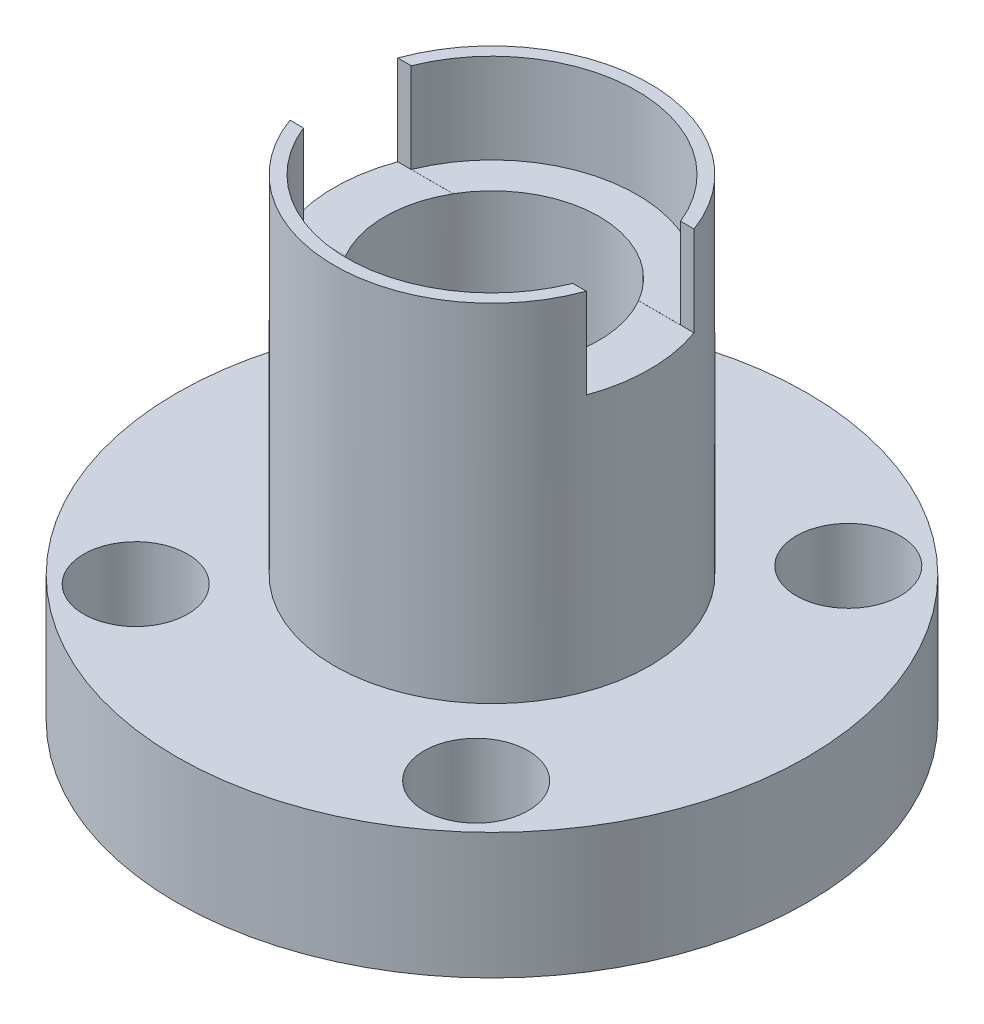
SolidWorks part; units mm, degrees
ref_plane "前视基准面" through (0, 0, 0) normal (0, 0, 1) x (1, 0, 0)
ref_plane "上视基准面" through (0, 0, 0) normal (0, 1, 0) x (1, 0, 0)
ref_plane "右视基准面" through (0, 0, 0) normal (1, 0, 0) x (0, 0, -1)
sketch "草图1" plane through (0, 0, 0) normal (0, 1, 0) x (1, 0, 0)
  circle A0 centre (0, 0) radius 10
extrude "凸台-拉伸1" add sketch "草图1" along normal blind 4
sketch "草图2" plane through (0, 0, 0) normal (0, -1, 0) x (1, 0, 0)
  line L1 (-5.4001, 5.9024) -> (5.4001, 5.9024) construction
  line L2 (-5.4001, 5.9024) -> (-5.4001, -5.9024) construction
  line L3 (-5.4001, -5.9024) -> (5.4001, -5.9024) construction
  line L4 (5.4001, 5.9024) -> (5.4001, -5.9024) construction
  line L5 (0, -5.9024) -> (0, 5.9024) construction
  line L6 (-5.4001, 0) -> (5.4001, 0) construction
  point P0 (0, 0)
  dimension "D1" = 16
  dimension "D2" = 16
sketch "草图4" plane through (0, 0, 0) normal (0, -1, 0) x (-1, 0, 0)
  circle A0 centre (0, 0) radius 8.0289 construction
  circle A1 centre (5.4001, -5.9024) radius 1.65
  circle A2 centre (-5.4001, -5.9024) radius 1.65
  circle A3 centre (-5.4001, 5.9024) radius 1.65
  circle A4 centre (5.4001, 5.9024) radius 1.65
extrude "切除-拉伸1" cut sketch "草图4" against normal blind 4
sketch "草图5" plane through (0, 4, 0) normal (0, 1, 0) x (1, 0, 0)
  circle A0 centre (0, 0) radius 5
extrude "凸台-拉伸2" add sketch "草图5" along normal blind 11
sketch "草图6" plane through (0, 15, 0) normal (0, 1, 0) x (1, 0, 0)
  circle A0 centre (0, 0) radius 3.5 construction
hole_wizard "M8 螺纹孔1" positions "3D草图1" profile "草图7" tap size "M8" standard "GB" end condition through all
sketch3d "3D草图1"
  point P0 (0, 0, 0)
  point P3 (0, 0, 0)
  point P5 (0, 15, 0)
sketch "草图7" plane through (0, 15, 0) normal (1, 0, 0) x (0, 0, 1)
  line L0 (0, 0) -> (0, 15)
  line L1 (0, 15) -> (3.4, 15)
  line L2 (3.4, 15) -> (3.4, 0)
  line L5 (3.4, 0) -> (0, 0)
  line L11 (0, -6.35) -> (0, 107.95) construction
  dimension "通孔螺纹孔钻头直径" = 6.8
  dimension "通孔螺纹孔钻头深度" = 15
cosmetic thread "孔螺蚊线1" parameters "D2"=8
cosmetic thread "孔螺蚊线2" parameters "D2"=8
cosmetic thread "孔螺蚊线3" parameters "D2"=8
sketch3d "3D草图2"
  point P0 (4.998, 11.2809, 0.1427)
ref_plane "基准面1" through (4.998, 0, 0) normal (1, 0, 0) x (0, 0, -1)
sketch "草图11" plane through (4.998, 0, 0) normal (1, 0, 0) x (0, 0, -1)
  line L0 (0, 15) -> (0, 13.5975) construction
  line L2 (3.4, 15) -> (-3.4, 15) construction
  line L4 (-1.7089, 15.0475) -> (1.7089, 15.0475)
  line L5 (-1.7089, 15.0475) -> (-1.7089, 12.1475)
  line L6 (-1.7089, 12.1475) -> (1.7089, 12.1475)
  line L7 (1.7089, 15.0475) -> (1.7089, 12.1475)
  line L8 (0, 12.1475) -> (0, 15.0475) construction
  line L9 (-1.7089, 13.5975) -> (1.7089, 13.5975) construction
  dimension "D1" = 2.9
extrude "切除-拉伸4" cut sketch "草图11" against normal through all and the other way through all
sketch "草图12" plane through (0, 15, 0) normal (0, 1, 0) x (1, 0, 0)
  circle A0 centre (0, 0) radius 4.6
extrude "切除-拉伸5" cut sketch "草图12" against normal blind 2.85
